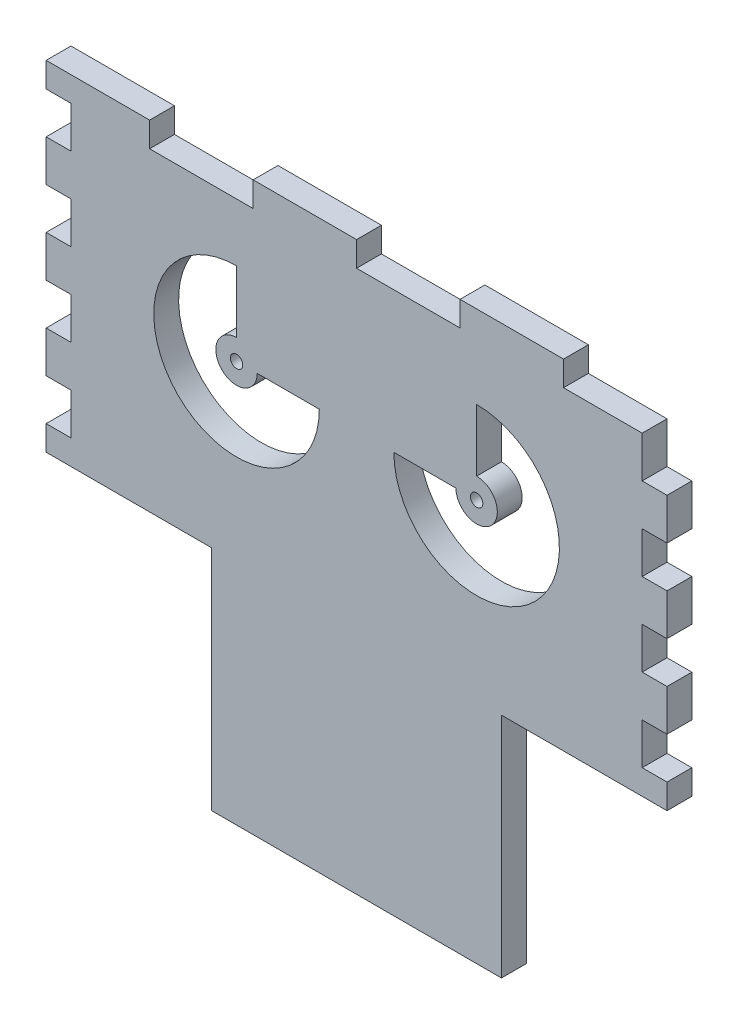
SolidWorks part; units mm, degrees
material "Pine"
ref_plane "Front Plane" through (0, 0, 0) normal (0, 0, 1) x (1, 0, 0)
ref_plane "Top Plane" through (0, 0, 0) normal (0, 1, 0) x (1, 0, 0)
ref_plane "Right Plane" through (0, 0, 0) normal (1, 0, 0) x (0, 0, -1)
sketch "Sketch1" plane through (0, 0, 0) normal (0, 0, 1) x (1, 0, 0)
  line L1 (75, -41) -> (-75, -41)
  line L2 (75, -41) -> (75, 41)
  line L3 (75, 41) -> (-75, 41)
  line L4 (-75, -41) -> (-75, 41)
  line L5 (75, -41) -> (-75, 41) construction
  line L6 (75, 41) -> (-75, -41) construction
  line L7 (-35, -41) -> (35, -41)
  line L8 (-35, -41) -> (-35, -96)
  line L9 (-35, -96) -> (35, -96)
  line L10 (35, -41) -> (35, -96)
  point P0 (0, 0)
  point P10 (0, -96)
  dimension "D1" = 150
  dimension "D2" = 82
  dimension "D3" = 55
  dimension "D4" = 70
  dimension "D5" = 0
extrude "Boss-Extrude1" add sketch "Sketch1" along normal blind 6 contours L10 L1 L8 L9 | L4 L1 L2 L3
sketch "Sketch2" plane through (0, 0, 6) normal (0, 0, 1) x (1, 0, 0)
  line L0 (-75, -41) -> (-75, 41) construction
  line L1 (-75, 35) -> (-69, 35)
  line L2 (-75, 35) -> (-75, 25)
  line L3 (-75, 25) -> (-69, 25)
  line L4 (-69, 35) -> (-69, 25)
  line L5 (75, 41) -> (-75, 41) construction
  line L6 (69, 35) -> (69, 25)
  line L7 (69, 35) -> (75, 35)
  line L8 (75, 35) -> (75, 25)
  line L9 (69, 25) -> (75, 25)
  line L10 (69, 15) -> (69, 5)
  line L11 (69, 15) -> (75, 15)
  line L12 (75, 15) -> (75, 5)
  line L13 (69, 5) -> (75, 5)
  line L14 (-75, 15) -> (-75, 5)
  line L15 (-75, 15) -> (-69, 15)
  line L16 (-69, 15) -> (-69, 5)
  line L17 (-75, 5) -> (-69, 5)
  line L18 (-75, -5) -> (-75, -15)
  line L19 (-75, -5) -> (-69, -5)
  line L20 (-69, -5) -> (-69, -15)
  line L21 (-75, -15) -> (-69, -15)
  line L22 (69, -5) -> (69, -15)
  line L23 (69, -5) -> (75, -5)
  line L24 (75, -5) -> (75, -15)
  line L25 (69, -15) -> (75, -15)
  line L26 (-75, -25) -> (-75, -35)
  line L27 (-75, -25) -> (-69, -25)
  line L28 (-69, -25) -> (-69, -35)
  line L29 (-75, -35) -> (-69, -35)
  line L30 (69, -25) -> (69, -35)
  line L31 (69, -25) -> (75, -25)
  line L32 (75, -25) -> (75, -35)
  line L33 (69, -35) -> (75, -35)
  dimension "D1" = 6
  dimension "D2" = 10
  dimension "D3" = 6
  dimension "D4" = 2
  dimension "D5" = 4
extrude "Cut-Extrude1" cut sketch "Sketch2" against normal blind 10
sketch "Sketch3" plane through (0, 0, 6) normal (0, 0, 1) x (1, 0, 0)
  line L0 (-9, 1) -> (-24, 1)
  line L1 (-29, 21) -> (-29, 6)
  line L2 (-35, -41) -> (-75, -41) construction
  line L3 (9, 1) -> (24, 1)
  line L4 (29, 21) -> (29, 6)
  line L26 (0, -3.3) -> (0, 3.3) construction
  circle A0 centre (-29, 1) radius 1.5
  circle A4 centre (29, 1) radius 1.5
  arc A7 (-9, 1) -> (-29, 21) centre (-29, 1) cw
  arc A8 (-24, 1) -> (-29, 6) centre (-29, 1) cw
  arc A9 (9, 1) -> (29, 21) centre (29, 1) ccw
  arc A10 (24, 1) -> (29, 6) centre (29, 1) ccw
  dimension "D2" = 3
  dimension "D3" = 20
  dimension "D4" = 20
  dimension "D1" = 29
  dimension "D5" = 20
  dimension "D6" = 15
  dimension "D7" = 42
extrude "Cut-Extrude2" cut sketch "Sketch3" against normal blind 6
sketch "Sketch4" plane through (0, 0, 6) normal (0, 0, 1) x (1, 0, 0)
  line L0 (25, 41) -> (25, 35)
  line L1 (75, 41) -> (50, 41)
  line L2 (75, 41) -> (75, 35)
  line L3 (75, 35) -> (50, 35)
  line L4 (50, 41) -> (50, 35)
  line L5 (25, 41) -> (0, 41)
  line L6 (0, 41) -> (0, 35)
  line L7 (25, 35) -> (0, 35)
  line L8 (-25, 41) -> (-25, 35)
  line L9 (-25, 41) -> (-50, 41)
  line L10 (-50, 41) -> (-50, 35)
  line L11 (-25, 35) -> (-50, 35)
  dimension "D1" = 25
  dimension "D2" = 6
  dimension "D3" = 3
extrude "Cut-Extrude3" cut sketch "Sketch4" against normal blind 6
